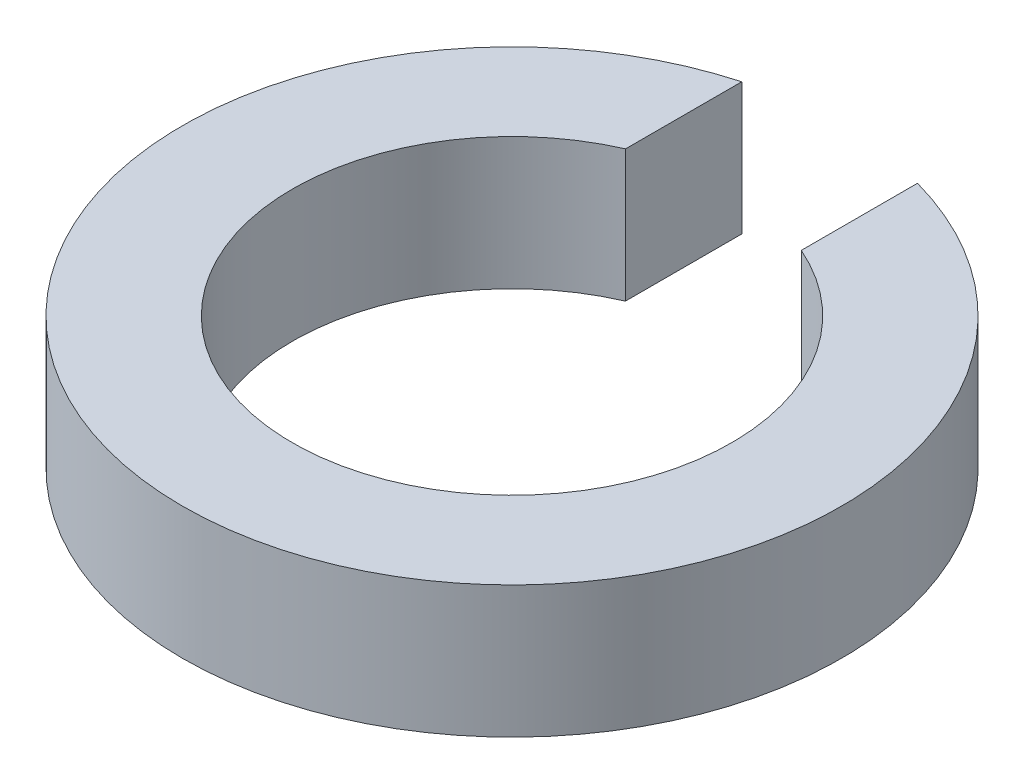
SolidWorks part; units mm, degrees
material "1060 Alloy"
ref_plane "Front Plane" through (0, 0, 0) normal (0, 0, 1) x (1, 0, 0)
ref_plane "Top Plane" through (0, 0, 0) normal (0, 1, 0) x (1, 0, 0)
ref_plane "Right Plane" through (0, 0, 0) normal (1, 0, 0) x (0, 0, -1)
sketch "Sketch1" plane through (0, 0, 0) normal (0, 1, 0) x (1, 0, 0)
  circle A0 centre (0, 0) radius 7.5
  circle A1 centre (0, 0) radius 5
  dimension "D1" = 15
  dimension "D2" = 10
extrude "Boss-Extrude1" add sketch "Sketch1" along normal blind 3
sketch "Sketch2" plane through (0, 3, 0) normal (0, 1, 0) x (1, 0, 0)
  line L0 (-2, 7.9423) -> (-2, 3.9423)
  line L1 (-2, 7.9423) -> (2, 7.9423)
  line L2 (-2, 3.9423) -> (2, 3.9423)
  line L3 (2, 7.9423) -> (2, 3.9423)
  line L4 (-2, 7.9423) -> (2, 3.9423) construction
  line L5 (-2, 3.9423) -> (2, 7.9423) construction
  line L6 (0, 5.9423) -> (0, 0) construction
  point P1 (0, 5.9423)
  dimension "D1" = 4
extrude "Cut-Extrude1" cut sketch "Sketch2" against normal blind 3.5
